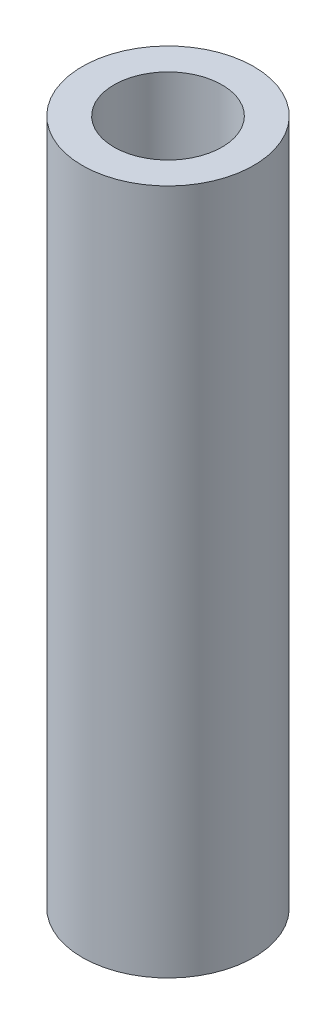
SolidWorks part; units mm, degrees
material "6061-T6 (SS)"
ref_plane "X-Y Datum" through (0, 0, 0) normal (0, 0, 1) x (1, 0, 0)
ref_plane "X-Z Datum" through (0, 0, 0) normal (0, 1, 0) x (1, 0, 0)
ref_plane "Y-Z Datum" through (0, 0, 0) normal (1, 0, 0) x (0, 0, -1)
sketch "Sketch1" plane through (0, 0, 0) normal (0, 1, 0) x (1, 0, 0)
  circle A0 centre (0, 0) radius 3.175
  circle A1 centre (0, 0) radius 2
  dimension "D1" = 6.35
  dimension "D2" = 4
extrude "Boss-Extrude1" add sketch "Sketch1" against normal blind 25.4
